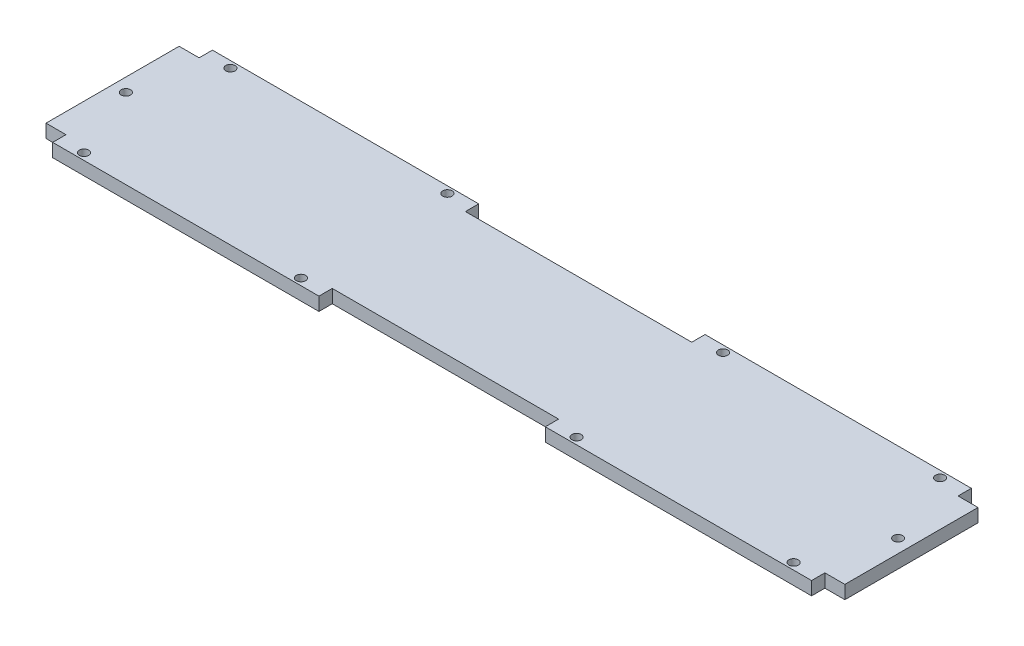
SolidWorks part; units mm, degrees
ref_plane "Front Plane" through (0, 0, 0) normal (0, 0, 1) x (1, 0, 0)
ref_plane "Top Plane" through (0, 0, 0) normal (0, 1, 0) x (1, 0, 0)
ref_plane "Right Plane" through (0, 0, 0) normal (1, 0, 0) x (0, 0, -1)
sketch "Sketch1" plane through (0, 0, 0) normal (0, 1, 0) x (1, 0, 0)
  line L0 (-92.5, -1005) -> (-92.5, 48995) construction
  line L1 (-142.5, -5) -> (-42.5, -5)
  line L2 (-142.5, -5) -> (-142.5, 0)
  line L3 (-142.5, 0) -> (-42.5, 0)
  line L4 (-42.5, -5) -> (-42.5, 0)
  line L5 (-150, 50) -> (150, 50)
  line L6 (-150, 50) -> (-150, 0)
  line L7 (-150, 0) -> (150, 0)
  line L8 (150, 50) -> (150, 0)
  line L9 (0, -1000) -> (0, 49000) construction
  line L10 (142.5, 0) -> (42.5, 0)
  line L11 (42.5, -5) -> (42.5, 0)
  line L12 (142.5, -5) -> (42.5, -5)
  line L13 (142.5, -5) -> (142.5, 0)
  line L14 (-1150, 25) -> (48850, 25) construction
  line L15 (142.5, 55) -> (142.5, 50)
  line L16 (142.5, 55) -> (42.5, 55)
  line L17 (42.5, 55) -> (42.5, 50)
  line L18 (142.5, 50) -> (42.5, 50)
  line L19 (-142.5, 50) -> (-42.5, 50)
  line L20 (-42.5, 55) -> (-42.5, 50)
  line L21 (-142.5, 55) -> (-42.5, 55)
  line L22 (-142.5, 55) -> (-142.5, 50)
  circle A0 centre (-51.75, -2.5) radius 1.75
  circle A2 centre (-133.25, -2.5) radius 1.75
  circle A3 centre (51.75, -2.5) radius 1.75
  circle A4 centre (133.25, -2.5) radius 1.75
  circle A5 centre (133.25, 52.5) radius 1.75
  circle A6 centre (51.75, 52.5) radius 1.75
  circle A7 centre (-51.75, 52.5) radius 1.75
  circle A8 centre (-133.25, 52.5) radius 1.75
  point P8 (0, 0)
  point P12 (-50, -2.5)
  point P16 (-135, -2.5)
  point P18 (-92.5, -5)
  point P20 (-42.5, -2.5)
  point P33 (-150, 25)
  dimension "D6" = 3.5
  dimension "D1" = 5
  dimension "D2" = 50
  dimension "D3" = 300
  dimension "D4" = 7.5
  dimension "D5" = 50
  dimension "D7" = 15
extrude "Boss-Extrude1" add sketch "Sketch1" along normal blind 5 contours L8 L5 L6 L7 L3 | L1 L4 L3 L2 A0 A2 | L12 L13 L7 L11 A4 A3 | L19 L20 L21 L22 | L15 L18 L17 L16 | A8 | A7 | A6 | A5
sketch "Sketch2" plane through (0, 5, 0) normal (0, 1, 0) x (1, 0, 0)
  line L0 (-150, 50) -> (-150, 0) construction
  line L1 (0, -1000) -> (0, 49000) construction
  circle A0 centre (-145, 25) radius 1.75
  circle A1 centre (145, 25) radius 1.75
  point P5 (-150, 25)
  dimension "D1" = 3.5
  dimension "D2" = 5
extrude "Cut-Extrude1" cut sketch "Sketch2" against normal blind 10
